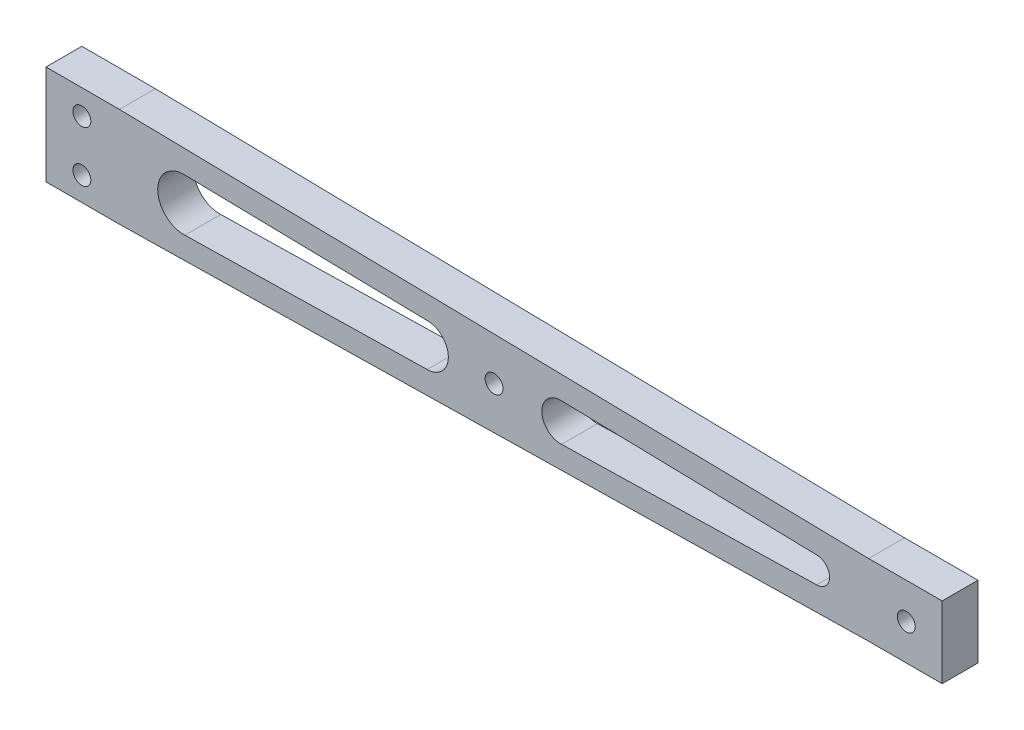
SolidWorks part; units mm, degrees
material "1060-H12"
ref_plane "Płaszczyzna przednia" through (0, 0, 0) normal (0, 0, 1) x (1, 0, 0)
ref_plane "Płaszczyzna górna" through (0, 0, 0) normal (0, 1, 0) x (1, 0, 0)
ref_plane "Płaszczyzna prawa" through (0, 0, 0) normal (1, 0, 0) x (0, 0, -1)
sketch "Model" plane through (0, 0, 0) normal (0, 0, 1) x (1, 0, 0)
  line L0 (229.5737, 20) -> (20.5737, 24)
  line L1 (250.0737, 20) -> (229.5737, 20)
  line L2 (250.0737, 0) -> (250.0737, 20)
  line L3 (250.0737, 0) -> (229.5737, 0)
  line L4 (229.5737, 0) -> (20.5737, -3.7576)
  line L5 (0.0737, -3.7576) -> (20.5737, -3.7576)
  line L6 (215.0574, 13.6212) -> (143.8977, 15.259)
  line L7 (143.8977, 4.741) -> (215.0574, 6.3788)
  line L8 (106.3982, 15.9145) -> (38.8063, 17.2706)
  line L9 (38.8063, 2.7294) -> (106.3982, 4.0855)
  line L10 (0.0737, 24) -> (0.0737, -3.7576)
  line L11 (0.0737, 24) -> (20.5737, 24)
  circle A0 centre (10.0737, 17.1212) radius 2.5
  circle A1 centre (240.0737, 10) radius 2.5
  circle A2 centre (10.0737, 2.8788) radius 2.5
  circle A3 centre (125.0737, 10) radius 2.5
  arc A4 (215.0574, 6.3788) -> (215.0574, 13.6212) centre (215.0574, 10) ccw
  arc A5 (143.8977, 15.259) -> (143.8977, 4.741) centre (143.6555, 10) ccw
  arc A6 (38.8063, 17.2706) -> (38.8063, 2.7294) centre (38.5144, 10) ccw
  arc A7 (106.3982, 4.0855) -> (106.3982, 15.9145) centre (106.3982, 10) ccw
extrude "Dodanie-wyciągnięcie1" add sketch "Model" along normal blind 10
